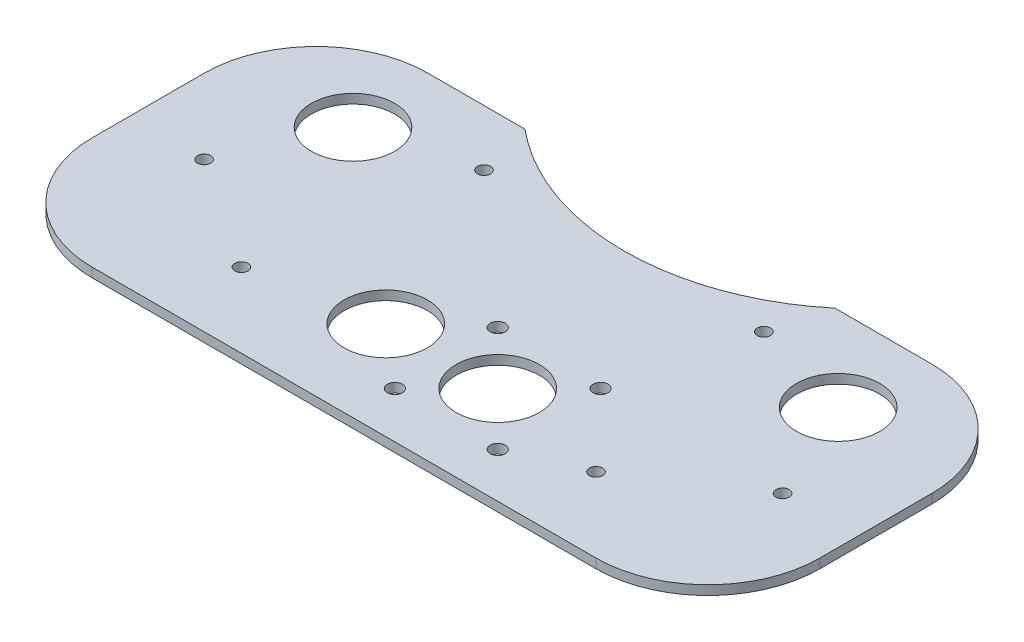
SolidWorks part; units mm, degrees
ref_plane "Front" through (0, 0, 0) normal (0, 0, 1) x (1, 0, 0)
ref_plane "Top" through (0, 0, 0) normal (0, 1, 0) x (1, 0, 0)
ref_plane "Right" through (0, 0, 0) normal (1, 0, 0) x (0, 0, -1)
sketch "Sketch1" plane through (0, 0, 0) normal (0, 1, 0) x (1, 0, 0)
  line L0 (-123.825, -57.15) -> (123.825, -57.15)
  line L1 (123.825, -57.15) -> (123.825, 57.15)
  line L2 (123.825, 57.15) -> (52.7471, 57.15)
  line L3 (-123.825, -57.15) -> (-123.825, 57.15)
  line L4 (-123.825, 57.15) -> (-52.7471, 57.15)
  arc A0 (-52.7471, 57.15) -> (52.7471, 57.15) centre (0, 120.65) ccw
  point P8 (0, -57.15)
  point P11 (123.825, 0)
  dimension "D1" = 165.1
  dimension "D2" = 114.3
  dimension "D3" = 247.65
  dimension "D4" = 63.5
extrude "Boss-Extrude1" add sketch "Sketch1" along normal blind 3.175 contours A0 L2 L1 L0 L3 L4
hole_wizard "1 (1.115) Dowel Hole1" positions "Sketch2" profile "Sketch3" hole size "1" standard "ANSI Inch" end condition through all
sketch "Sketch2" plane through (0, 3.175, 0) normal (0, 1, 0) x (1, 0, 0)
  circle A0 centre (19.05, -23.9069) radius 6.35 construction
  point P0 (19.05, -23.9069)
sketch "Sketch3" plane through (19.05, 3.175, 23.9069) normal (1, 0, 0) x (0, 0, 1)
  line L0 (0, 0) -> (0, 3.175)
  line L1 (0, 3.175) -> (14.1605, 3.175)
  line L2 (14.1605, 3.175) -> (14.1605, 0)
  line L5 (14.1605, 0) -> (0, 0)
  line L11 (0, -6.35) -> (0, 107.95) construction
  dimension "Thru Hole Dia." = 28.321
  dimension "Thru Hole Depth" = 3.175
hole_wizard "#10 Clearance Hole1" positions "Sketch4" profile "Sketch6" hole size "#10" standard "ANSI Inch" end condition up to next
sketch "Sketch4" plane through (0, 3.175, 0) normal (0, 1, 0) x (1, 0, 0)
  circle A0 centre (1.55, -41.4069) radius 2.5527 construction
  circle A1 centre (36.55, -6.4069) radius 2.5527 construction
  circle A2 centre (37.0105, -41.8675) radius 2.5527 construction
  circle A3 centre (1.0895, -5.9464) radius 2.5527 construction
  point P16 (1.55, -41.4069)
  point P18 (36.55, -6.4069)
  point P25 (1.0895, -5.9464)
  point P27 (37.0105, -41.8675)
sketch "Sketch6" plane through (1.55, 3.175, 41.4069) normal (1, 0, 0) x (0, 0, 1)
  line L0 (0, 0) -> (0, 3.175)
  line L1 (0, 3.175) -> (2.5527, 3.175)
  line L2 (2.5527, 3.175) -> (2.5527, 0)
  line L5 (2.5527, 0) -> (0, 0)
  line L11 (0, -6.35) -> (0, 107.95) construction
  dimension "Thru Hole Dia." = 5.1054
  dimension "Thru Hole Depth" = 3.175
fillet "Fillet1" radius 38.1 4 edges at (-123.825, 1.5875, -57.15) (-123.825, 1.5875, 57.15) (123.825, 1.5875, 57.15) (123.825, 1.5875, -57.15)
hole_wizard "1 (1.115) Dowel Hole2" positions "Sketch7" profile "Sketch8" hole size "1" standard "ANSI Inch" end condition through all
sketch "Sketch7" plane through (0, -34.925, 0) normal (0, -1, 0) x (-1, 0, 0)
  line L0 (82.55, 28.448) -> (-82.55, 28.448) construction
  point P0 (82.55, 28.448)
  point P2 (-82.55, 28.448)
sketch "Sketch8" plane through (-82.55, -34.925, -28.448) normal (1, 0, 0) x (0, 0, -1)
  line L0 (0, 0) -> (0, 38.1)
  line L1 (0, 38.1) -> (14.1605, 38.1)
  line L2 (14.1605, 38.1) -> (14.1605, 0)
  line L3 (14.1605, 0) -> (0, 0)
  line L4 (0, -6.35) -> (0, 107.95) construction
  dimension "Thru Hole Dia." = 28.321
  dimension "Thru Hole Depth" = 38.1
hole_wizard "#8 Clearance Hole" positions "Sketch9" profile "Sketch10" hole size "#8" standard "ANSI Inch" end condition through all
sketch "Sketch9" plane through (0, 3.175, 0) normal (0, 1, 0) x (1, 0, 0)
  line L3 (-47.625, 38.1) -> (47.625, 38.1) construction
  line L5 (0, 0) -> (0, 73.5517) construction
  point P0 (-98.425, -6.35)
  point P2 (-60.325, -31.75)
  point P13 (-47.625, 38.1)
  point P15 (47.625, 38.1)
  point P34 (0, 0)
  point P35 (60.325, -31.75)
  point P36 (98.425, -6.35)
sketch "Sketch10" plane through (-98.425, 3.175, 6.35) normal (1, 0, 0) x (0, 0, 1)
  line L0 (0, 0) -> (0, 3.175)
  line L1 (0, 3.175) -> (2.2479, 3.175)
  line L2 (2.2479, 3.175) -> (2.2479, 0)
  line L3 (2.2479, 0) -> (0, 0)
  line L4 (0, -6.35) -> (0, 107.95) construction
  dimension "Thru Hole Dia." = 4.4958
  dimension "Thru Hole Depth" = 3.175
hole_wizard "1 (1.115) Dowel Hole3" positions "Sketch11" profile "Sketch12" hole size "1" standard "ANSI Inch"
sketch "Sketch11" plane through (0, -34.925, 0) normal (0, -1, 0) x (-1, 0, 0)
  line L0 (-19.05, -23.9069) -> (19.05, -23.9069) construction
  point P0 (19.05, -23.9069)
sketch "Sketch12" plane through (-19.05, -34.925, 23.9069) normal (1, 0, 0) x (0, 0, -1)
  line L0 (0, 0) -> (0, 38.1)
  line L1 (0, 38.1) -> (14.1605, 38.1)
  line L2 (14.1605, 38.1) -> (14.1605, 0)
  line L3 (14.1605, 0) -> (0, 0)
  line L4 (0, 38.1) -> (-14.1605, 38.1) construction
  line L5 (0, -6.35) -> (0, 107.95) construction
  dimension "Hole Dia." = 28.321
  dimension "Hole Depth" = 38.1
  dimension "Drill Angle" = 180
